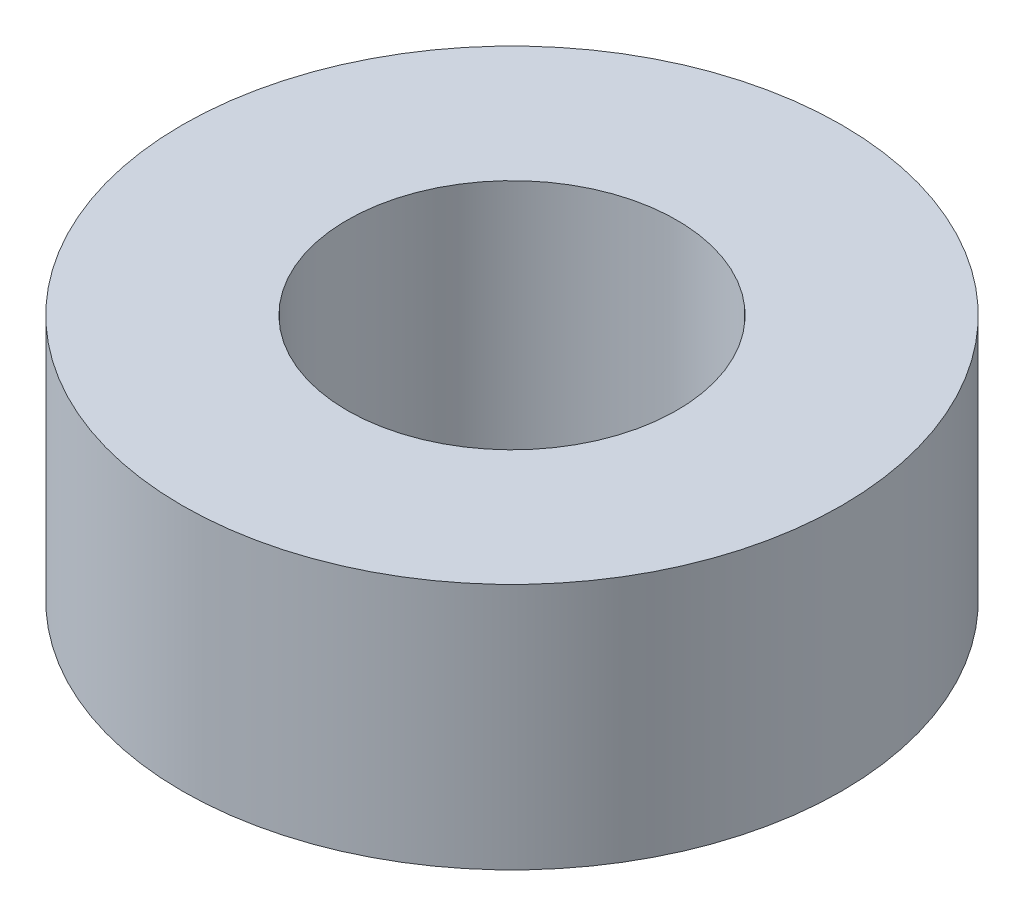
SolidWorks part; units mm, degrees
ref_plane "Front Plane" through (0, 0, 0) normal (0, 0, 1) x (1, 0, 0)
ref_plane "Top Plane" through (0, 0, 0) normal (0, 1, 0) x (1, 0, 0)
ref_plane "Right Plane" through (0, 0, 0) normal (1, 0, 0) x (0, 0, -1)
other "Bounding Box"
ref_plane "Default Plane" through (-8.9266, -12.7485, 0) normal (-0.1736, 0.9848, 0) x (0.9848, 0.1736, 0)
sketch "Sketch1" plane through (0, 0, 0) normal (0, 1, 0) x (1, 0, 0)
  circle A0 centre (0, 0) radius 2
  circle A1 centre (0, 0) radius 4
  dimension "D1" = 4
  dimension "D2" = 8
extrude "Boss-Extrude1" add sketch "Sketch1" along normal mid plane 3
